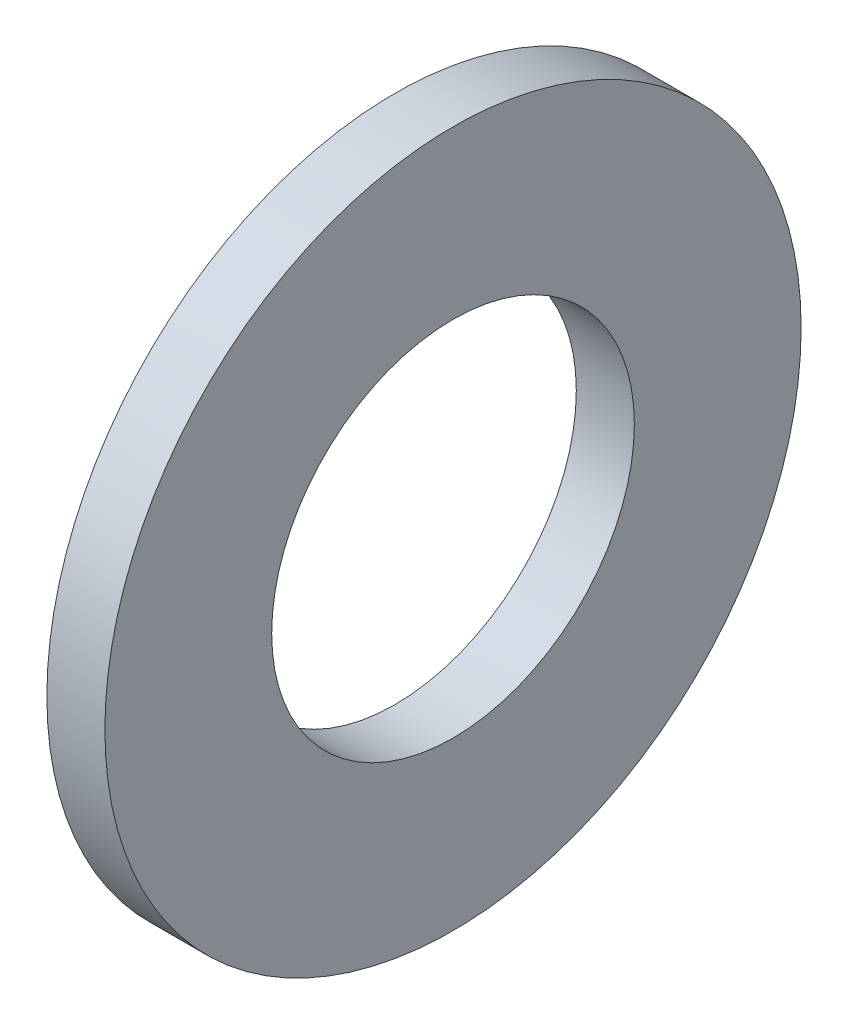
SolidWorks part; units mm, degrees
ref_plane "Front Plane" through (0, 0, 0) normal (0, 0, 1) x (1, 0, 0)
ref_plane "Top Plane" through (0, 0, 0) normal (0, 1, 0) x (1, 0, 0)
ref_plane "Right Plane" through (0, 0, 0) normal (1, 0, 0) x (0, 0, -1)
sketch "Sketch1" plane through (0, 0, 0) normal (1, 0, 0) x (0, 0, -1)
  circle A0 centre (0, 0) radius 6
  circle A1 centre (0, 0) radius 3.125
  dimension "D1" = 6.25
  dimension "D2" = 12
extrude "Boss-Extrude1" add sketch "Sketch1" along normal mid plane 1
